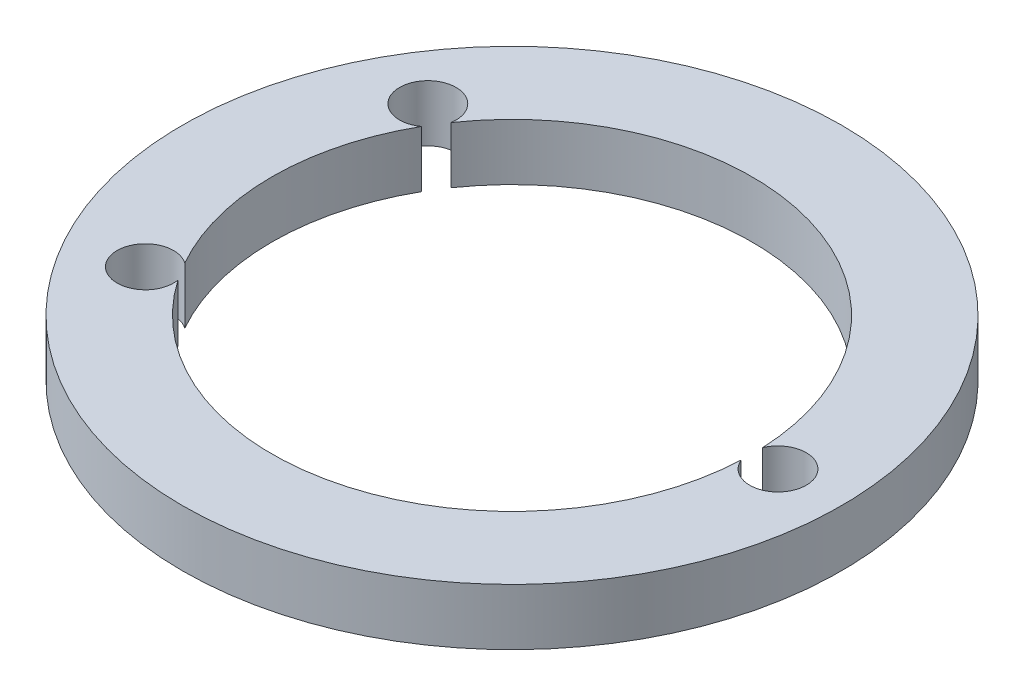
SolidWorks part; units mm, degrees
ref_plane "前视基准面" through (0, 0, 0) normal (0, 0, 1) x (1, 0, 0)
ref_plane "上视基准面" through (0, 0, 0) normal (0, 1, 0) x (1, 0, 0)
ref_plane "右视基准面" through (0, 0, 0) normal (1, 0, 0) x (0, 0, -1)
sketch "草图1" plane through (0, 0, 0) normal (0, 1, 0) x (1, 0, 0)
  line L0 (0, 0) -> (41.8537, 0) construction
  line L1 (0, 0) -> (0, 19.6189) construction
  circle A0 centre (0, 0) radius 28.25 construction
  arc A1 (-20.9822, 14.4913) -> (-22.1915, 12.5613) centre (-23.9387, 15) ccw
  arc A2 (-20.9822, -14.4913) -> (-22.1915, -12.5613) centre (-23.9387, -15) cw
  arc A3 (25.4746, -1.1388) -> (25.4746, 1.1388) centre (28.25, 0) ccw
  arc A5 (-22.1915, 12.5613) -> (-22.1915, -12.5613) centre (0, 0) ccw
  arc A6 (25.4746, 1.1388) -> (-20.9822, 14.4913) centre (0, 0) ccw
  arc A7 (-20.9822, -14.4913) -> (25.4746, -1.1388) centre (0, 0) ccw
  circle A8 centre (0, 0) radius 35
  dimension "D1" = 56.5
  dimension "D2" = 30
  dimension "D3" = 6
  dimension "D4" = 3
  dimension "D6" = 51
  dimension "D9" = 70
  dimension "D5" = 0
extrude "凸台-拉伸1" add sketch "草图1" along normal blind 6
